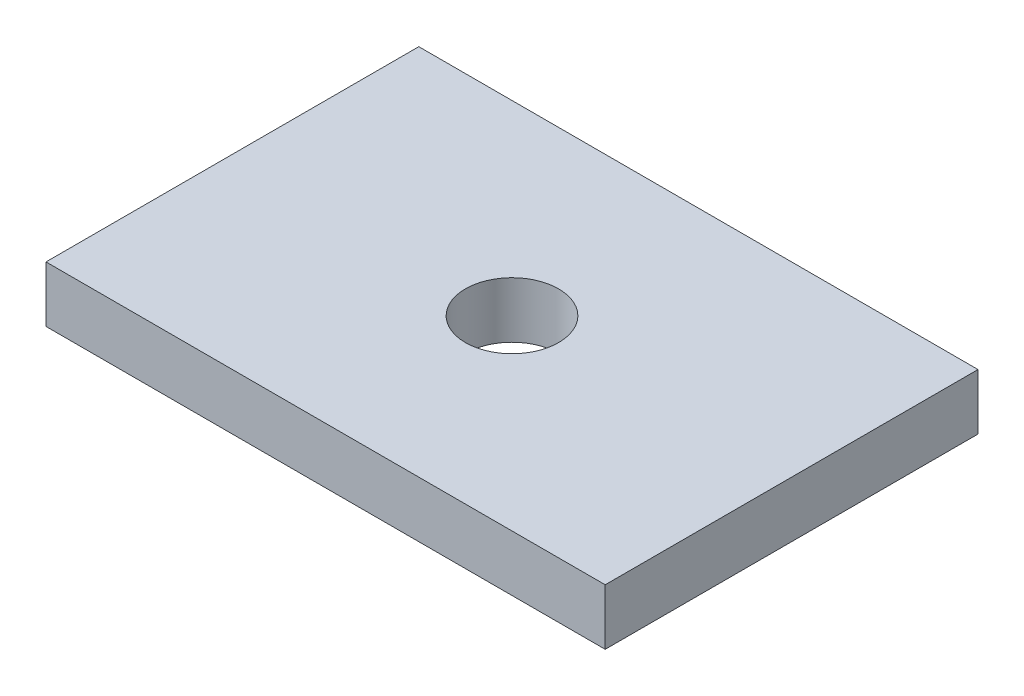
SolidWorks part; units mm, degrees
ref_plane "Front Plane" through (0, 0, 0) normal (0, 0, 1) x (1, 0, 0)
ref_plane "Top Plane" through (0, 0, 0) normal (0, 1, 0) x (1, 0, 0)
ref_plane "Right Plane" through (0, 0, 0) normal (1, 0, 0) x (0, 0, -1)
sketch "Sketch1" plane through (0, 0, 0) normal (0, 1, 0) x (1, 0, 0)
  line L1 (-30, 20) -> (30, 20)
  line L2 (-30, 20) -> (-30, -20)
  line L3 (-30, -20) -> (30, -20)
  line L4 (30, 20) -> (30, -20)
  line L5 (-30, 20) -> (30, -20) construction
  line L6 (-30, -20) -> (30, 20) construction
  point P0 (0, 0)
  dimension "D1" = 60
  dimension "D2" = 40
extrude "Boss-Extrude1" add sketch "Sketch1" along normal blind 6
sketch "Sketch2" plane through (0, 6, 0) normal (0, 1, 0) x (1, 0, 0)
  circle A0 centre (0, 0) radius 5
  dimension "D1" = 10
extrude "Cut-Extrude1" cut sketch "Sketch2" against normal blind 6
sketch "Sketch3" plane through (0, 0, 0) normal (0, 1, 0) x (1, 0, 0)
  circle A0 centre (0, 0) radius 12.5
  dimension "D1" = 25
